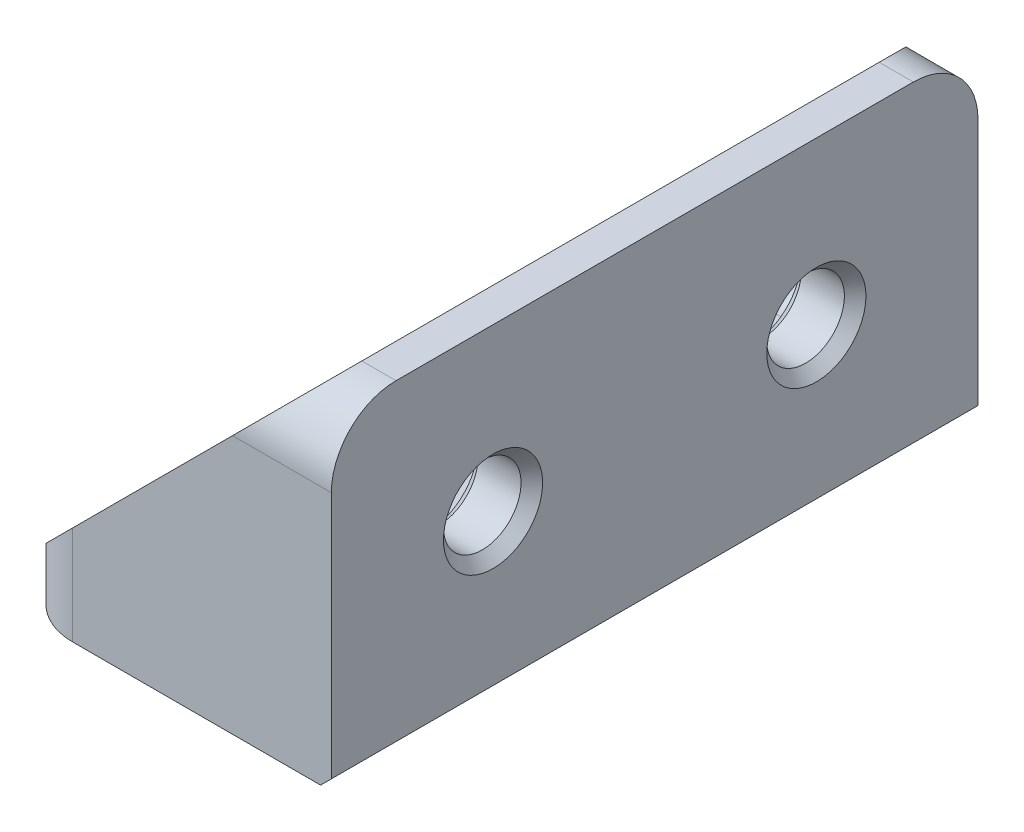
SolidWorks part; units mm, degrees
ref_plane "Front Plane" through (0, 0, 0) normal (0, 0, 1) x (1, 0, 0)
ref_plane "Top Plane" through (0, 0, 0) normal (0, 1, 0) x (1, 0, 0)
ref_plane "Right Plane" through (0, 0, 0) normal (1, 0, 0) x (0, 0, -1)
sketch "Sketch1" plane through (0, 0, 0) normal (0, 0, 1) x (1, 0, 0)
  line L0 (0, 0) -> (0, 15)
  line L1 (0, 15) -> (-3, 15)
  line L2 (-3, 15) -> (-15, 3)
  line L3 (-15, 3) -> (-15, 0)
  line L4 (-15, 0) -> (0, 0)
  dimension "D1" = 45
  dimension "D2" = 15
  dimension "D3" = 15
  dimension "D4" = 3
extrude "Boss-Extrude1" add sketch "Sketch1" along normal blind 30
sketch "Sketch3" plane through (0, 0, 30) normal (0, 0, 1) x (1, 0, 0)
  line L0 (-15, 3) -> (-3, 3)
  line L1 (-3, 3) -> (-3, 15)
  line L2 (-3, 15) -> (-15, 3)
extrude "Cut-Extrude1" cut sketch "Sketch3" against normal blind 25 from offset 2.5 offset against normal yes
sketch "Sketch4" plane through (-3, 0, 0) normal (-1, 0, 0) x (0, 0, 1)
  line L0 (2.5, 15) -> (27.5, 15) construction
  line L1 (0, 0) -> (0, 15) construction
  line L2 (30, 0) -> (30, 15) construction
  circle A0 centre (7.5, 7.5) radius 1.8
  circle A1 centre (22.5, 7.5) radius 1.8
  point P8 (0, 0)
  dimension "D1" = 3.6
  dimension "D2" = 7.5
  dimension "D3" = 7.5
  dimension "D4" = 7.5
extrude "Cut-Extrude2" cut sketch "Sketch4" against normal blind 25
fillet "Fillet1" radius 1 5 edges at (-9, 3, 27.5) (-3, 9, 27.5) (-3, 3, 15) (-9, 3, 2.5) (-3, 9, 2.5)
fillet "Fillet2" radius 3 4 edges at (-1.5, 15, 30) (-15, 1.5, 30) (-15, 1.5, 0) (-1.5, 15, 0)
sketch "Sketch5" plane through (0, 3, 0) normal (0, 1, 0) x (1, 0, 0)
  line L0 (-15, -3.5) -> (-15, -26.5) construction
  circle A0 centre (-10, -15) radius 2
  circle A1 centre (-10, -15) radius 5 construction
  point P5 (0, 0)
  point P6 (-15, -15)
  dimension "D1" = 4
  dimension "D2" = 10
  dimension "D3" = 5
extrude "Cut-Extrude3" cut sketch "Sketch5" against normal blind 25
sketch "Sketch6" plane through (0, 0, 0) normal (0, 0, -1) x (-1, 0, 0)
  line L0 (-1.604, 18.1898) -> (17.8351, -1.2493)
  line L1 (17.8351, -1.2493) -> (19.9564, 0.872)
  line L2 (19.9564, 0.872) -> (-1.0741, 21.9025)
  line L3 (-1.0741, 21.9025) -> (-1.604, 18.1898)
  line L4 (6, 12) -> (12, 6) construction
  dimension "D1" = 1
  dimension "D2" = 3
extrude "Cut-Extrude4" cut sketch "Sketch6" against normal through all
chamfer "Chamfer1" distance 0.5 angle 45 7 edges at (-10, 0, 17) (0, 7.5, 9.3) (0, 7.5, 24.3) (-10, 3, 17) (-3, 7.5, 24.3) (-3, 7.5, 9.3) (0, 0, 15)
